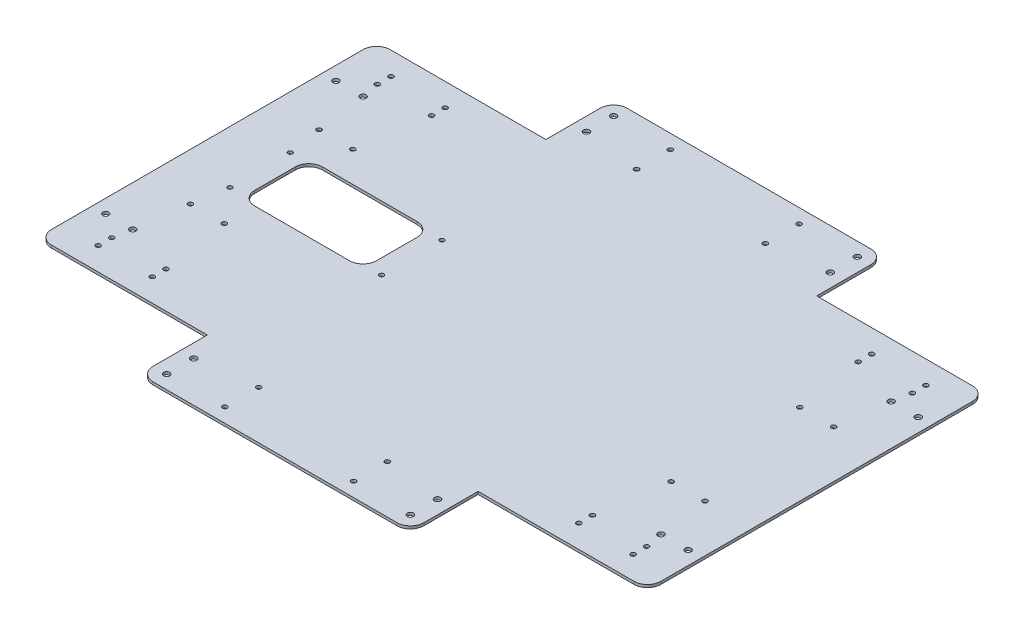
SolidWorks part; units mm, degrees
material "1060 Alloy"
ref_plane "Front Plane" through (0, 0, 0) normal (0, 0, 1) x (1, 0, 0)
ref_plane "Top Plane" through (0, 0, 0) normal (0, 1, 0) x (1, 0, 0)
ref_plane "Right Plane" through (0, 0, 0) normal (1, 0, 0) x (0, 0, -1)
sketch "Sketch5" plane through (0, 0, 0) normal (0, 1, 0) x (1, 0, 0)
  line L1 (0, 0) -> (450, 0)
  line L2 (0, 0) -> (0, 350)
  line L3 (0, 350) -> (450, 350)
  line L4 (450, 0) -> (450, 350)
  dimension "D1" = 450
  dimension "D2" = 350
extrude "Boss-Extrude1" add sketch "Sketch5" along normal blind 2 contours L2 L3 L4 L1
fillet "Fillet1" radius 10 4 edges at (0, 1, -350) (450, 1, -350) (450, 1, 0) (0, 1, 0)
sketch "Sketch6" plane through (0, 2, 0) normal (0, 1, 0) x (1, 0, 0)
  line L0 (95, 0) -> (95, 350) construction
  line L1 (140, 190) -> (140, 160)
  line L2 (130, 200) -> (60, 200)
  line L3 (50, 190) -> (50, 160)
  line L4 (130, 150) -> (60, 150)
  line L5 (10, 350) -> (440, 350) construction
  line L6 (50, 175) -> (140, 175) construction
  line L7 (95, 200) -> (95, 150) construction
  line L9 (0, 10) -> (0, 340) construction
  line L10 (10, 0) -> (440, 0) construction
  arc A0 (60, 200) -> (50, 190) centre (60, 190) ccw
  arc A1 (50, 160) -> (60, 150) centre (60, 160) ccw
  arc A2 (140, 160) -> (130, 150) centre (130, 160) cw
  arc A3 (140, 190) -> (130, 200) centre (130, 190) ccw
  point P20 (95, 175)
  point P21 (95, 175)
  dimension "D1" = 10
  dimension "D2" = 50
  dimension "D3" = 90
  dimension "D4" = 95
extrude "Cut-Extrude1" cut sketch "Sketch6" against normal through all
sketch "Sketch7" plane through (0, 2, 0) normal (0, 1, 0) x (1, 0, 0)
  line L0 (10, 0) -> (440, 0) construction
  line L1 (0, 10) -> (0, 340) construction
  line L2 (135, 30) -> (135, 10) construction
  line L3 (10, 90) -> (30, 90) construction
  line L4 (225, 350) -> (225, 0) construction
  line L5 (10, 350) -> (440, 350) construction
  line L6 (0, 175) -> (450, 175) construction
  line L7 (450, 10) -> (450, 340) construction
  point P0 (135, 10)
  point P1 (135, 30)
  point P2 (10, 90)
  point P3 (30, 90)
  point P20 (315, 10)
  point P21 (315, 30)
  point P22 (420, 90)
  point P23 (440, 90)
  point P24 (440, 260)
  point P25 (420, 260)
  point P26 (315, 340)
  point P27 (315, 320)
  point P28 (135, 340)
  point P29 (135, 320)
  point P30 (30, 260)
  point P31 (10, 260)
  dimension "D1" = 10
  dimension "D2" = 20
  dimension "D3" = 10
  dimension "D4" = 20
  dimension "D5" = 135
  dimension "D6" = 90
hole_wizard "M4 Clearance Hole1" positions "Sketch7" profile "Sketch8" hole size "M4" standard "ANSI Metric" end condition through all
sketch "Sketch8" plane through (135, 2, -10) normal (1, 0, 0) x (0, 0, 1)
  line L0 (0, 0) -> (0, 2)
  line L1 (0, 2) -> (2.25, 2)
  line L2 (2.25, 2) -> (2.25, 0)
  line L5 (2.25, 0) -> (0, 0)
  line L11 (0, -6.35) -> (0, 107.95) construction
  dimension "Thru Hole Dia." = 4.5
  dimension "Thru Hole Depth" = 2
sketch "Sketch13" plane through (0, 2, 0) normal (0, 1, 0) x (1, 0, 0)
  line L0 (0, 175) -> (450, 175) construction
  line L1 (0, 10) -> (0, 340) construction
  line L2 (450, 10) -> (450, 340) construction
  line L3 (225, 175) -> (225, 227.8107) construction
  line L4 (35, 222.5) -> (60, 222.5) construction
  line L5 (35, 222.5) -> (35, 127.5) construction
  line L6 (177.5, 339.5) -> (272.5, 339.5) construction
  line L7 (177.5, 339.5) -> (177.5, 314.5) construction
  circle A0 centre (272.5, 35.5) radius 1.75
  circle A1 centre (272.5, 10.5) radius 1.75
  circle A2 centre (177.5, 35.5) radius 1.75
  circle A3 centre (177.5, 10.5) radius 1.75
  arc A16 (272.5, 316.15) -> (272.5, 312.85) centre (272.5, 314.5) ccw construction
  arc A17 (272.5, 312.85) -> (272.5, 316.15) centre (272.5, 314.5) ccw construction
  arc A18 (272.5, 341.15) -> (272.5, 337.85) centre (272.5, 339.5) ccw construction
  arc A19 (272.5, 337.85) -> (272.5, 341.15) centre (272.5, 339.5) ccw construction
  arc A20 (177.5, 316.15) -> (177.5, 312.85) centre (177.5, 314.5) ccw construction
  arc A21 (177.5, 312.85) -> (177.5, 316.15) centre (177.5, 314.5) ccw construction
  arc A22 (177.5, 341.15) -> (177.5, 337.85) centre (177.5, 339.5) ccw construction
  arc A23 (177.5, 337.85) -> (177.5, 341.15) centre (177.5, 339.5) ccw construction
  arc A48 (272.5, 316.15) -> (272.5, 312.85) centre (272.5, 314.5) ccw construction
  arc A49 (272.5, 312.85) -> (272.5, 316.15) centre (272.5, 314.5) ccw construction
  arc A50 (272.5, 341.15) -> (272.5, 337.85) centre (272.5, 339.5) ccw construction
  arc A51 (272.5, 337.85) -> (272.5, 341.15) centre (272.5, 339.5) ccw construction
  arc A52 (177.5, 316.15) -> (177.5, 312.85) centre (177.5, 314.5) ccw construction
  arc A53 (177.5, 312.85) -> (177.5, 316.15) centre (177.5, 314.5) ccw construction
  arc A54 (177.5, 341.15) -> (177.5, 337.85) centre (177.5, 339.5) ccw construction
  arc A55 (177.5, 337.85) -> (177.5, 341.15) centre (177.5, 339.5) ccw construction
  circle A64 centre (35, 222.5) radius 1.75
  circle A65 centre (60, 222.5) radius 1.75
  circle A66 centre (60, 127.5) radius 1.75
  circle A67 centre (35, 127.5) radius 1.75
  circle A68 centre (177.5, 339.5) radius 1.75
  circle A69 centre (272.5, 339.5) radius 1.75
  circle A70 centre (272.5, 314.5) radius 1.75
  circle A71 centre (177.5, 314.5) radius 1.75
  circle A72 centre (415, 127.5) radius 1.75
  circle A73 centre (390, 127.5) radius 1.75
  circle A74 centre (390, 222.5) radius 1.75
  circle A75 centre (415, 222.5) radius 1.75
  point P9 (35, 175)
  dimension "D1" = 3.5
  dimension "D2" = 2
  dimension "D6" = 3.5
  dimension "D4" = 25
  dimension "D5" = 95
  dimension "D9" = 95
  dimension "D10" = 25
  dimension "D11" = 35
  dimension "D3" = 2
  dimension "D7" = 2
  dimension "D8" = 2
extrude "Cut-Extrude2" cut sketch "Sketch13" against normal through all
sketch "Sketch14" plane through (0, 2, 0) normal (0, 1, 0) x (1, 0, 0)
  line L0 (27.5, 76.9004) -> (67.5, 76.9004) construction
  line L1 (27.5, 76.9004) -> (27.5, 66.9004) construction
  line L2 (0, 175) -> (450, 175) construction
  line L3 (0, 10) -> (0, 340) construction
  line L4 (450, 10) -> (450, 340) construction
  line L5 (225, 175) -> (225, 224.2921) construction
  line L6 (10, 0) -> (440, 0) construction
  circle A16 centre (27.5, 76.9004) radius 1.75
  circle A17 centre (67.5, 76.9004) radius 1.75
  circle A18 centre (67.5, 66.9004) radius 1.75
  circle A19 centre (27.5, 66.9004) radius 1.75
  circle A20 centre (67.5, 283.0996) radius 1.75
  circle A21 centre (67.5, 273.0996) radius 1.75
  circle A22 centre (27.5, 283.0996) radius 1.75
  circle A23 centre (27.5, 273.0996) radius 1.75
  circle A24 centre (382.5, 273.0996) radius 1.75
  circle A25 centre (382.5, 283.0996) radius 1.75
  circle A26 centre (422.5, 283.0996) radius 1.75
  circle A27 centre (422.5, 273.0996) radius 1.75
  circle A28 centre (422.5, 66.9004) radius 1.75
  circle A29 centre (382.5, 66.9004) radius 1.75
  circle A30 centre (382.5, 76.9004) radius 1.75
  circle A31 centre (422.5, 76.9004) radius 1.75
  dimension "D1" = 3.5
  dimension "D4" = 40
  dimension "D5" = 10
  dimension "D6" = 27.5
  dimension "D7" = 76.9004
  dimension "D2" = 2
  dimension "D3" = 2
extrude "Cut-Extrude3" cut sketch "Sketch14" against normal through all
sketch "Sketch15" plane through (0, 2, 0) normal (0, 1, 0) x (1, 0, 0)
  line L0 (0, 175) -> (450, 175) construction
  line L1 (0, 350) -> (125, 350)
  line L2 (0, 350) -> (0, 300)
  line L3 (0, 300) -> (125, 300)
  line L4 (125, 350) -> (125, 300)
  line L5 (0, 350) -> (125, 300) construction
  line L6 (0, 300) -> (125, 350) construction
  line L7 (0, 10) -> (0, 340) construction
  line L8 (450, 10) -> (450, 340) construction
  line L9 (225, 175) -> (225, 236.2931) construction
  line L10 (0, 50) -> (125, 0) construction
  line L11 (0, 0) -> (125, 50) construction
  line L12 (125, 0) -> (125, 50)
  line L13 (0, 50) -> (125, 50)
  line L14 (0, 0) -> (0, 50)
  line L15 (0, 0) -> (125, 0)
  line L16 (450, 0) -> (325, 50) construction
  line L17 (450, 50) -> (325, 0) construction
  line L18 (450, 0) -> (325, 0)
  line L19 (450, 0) -> (450, 50)
  line L20 (450, 50) -> (325, 50)
  line L21 (325, 0) -> (325, 50)
  line L22 (450, 300) -> (325, 350) construction
  line L23 (450, 350) -> (325, 300) construction
  line L24 (325, 350) -> (325, 300)
  line L25 (450, 300) -> (325, 300)
  line L26 (450, 350) -> (450, 300)
  line L27 (450, 350) -> (325, 350)
  point P4 (62.5, 325)
  point P17 (62.5, 25)
  point P22 (387.5, 25)
  point P27 (387.5, 325)
  dimension "D1" = 50
  dimension "D2" = 125
extrude "Cut-Extrude4" cut sketch "Sketch15" against normal through all
fillet "Fillet2" radius 10 8 edges at (0, 1, -50) (125, 1, 0) (325, 1, 0) (450, 1, -50) (450, 1, -300) (325, 1, -350) (125, 1, -350) (0, 1, -300)
sketch "Sketch16" plane through (0, 2, 0) normal (0, 1, 0) x (1, 0, 0)
  line L0 (39, 197.3) -> (39, 152.7) construction
  line L1 (50, 175) -> (140, 175) construction
  line L2 (50, 190) -> (50, 160) construction
  line L3 (140, 160) -> (140, 190) construction
  line L4 (95, 175) -> (95, 183.1804) construction
  circle A0 centre (39, 197.3) radius 1.65
  circle A1 centre (39, 152.7) radius 1.65
  circle A2 centre (151, 152.7) radius 1.65
  circle A3 centre (151, 197.3) radius 1.65
  point P8 (39, 175)
  dimension "D2" = 3.3
  dimension "D1" = 44.6
  dimension "D3" = 56
extrude "Cut-Extrude5" cut sketch "Sketch16" against normal through all
